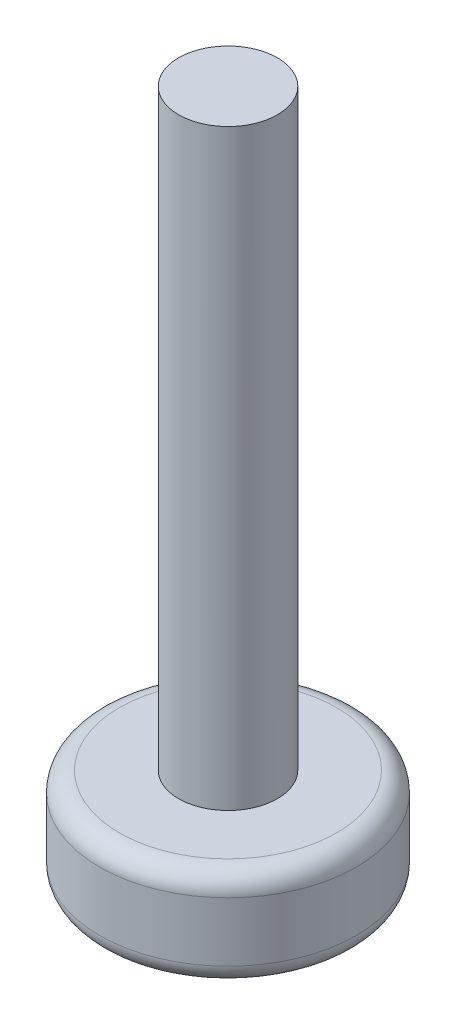
SolidWorks part; units mm, degrees
material "Nylon 101"
ref_plane "Front Plane" through (0, 0, 0) normal (0, 0, 1) x (1, 0, 0)
ref_plane "Top Plane" through (0, 0, 0) normal (0, 1, 0) x (1, 0, 0)
ref_plane "Right Plane" through (0, 0, 0) normal (1, 0, 0) x (0, 0, -1)
sketch "Sketch1" plane through (0, 0, 0) normal (0, 1, 0) x (1, 0, 0)
  circle A0 centre (0, 0) radius 2.5
  dimension "D1" = 5
extrude "Boss-Extrude1" add sketch "Sketch1" along normal blind 30
cosmetic thread "Cosmetic Thread1" parameters "D1"=30, "D2"=0.3
sketch "Sketch2" plane through (0, 0, 0) normal (0, 0, 1) x (1, 0, 0)
  line L0 (0, 0) -> (0, -5)
  line L1 (-5.5, 0) -> (0, 0)
  line L2 (-6.5, -1) -> (-6.5, -4)
  line L3 (-5.5, -5) -> (0, -5)
  arc A2 (-6.5, -4) -> (-5.5, -5) centre (-5.5, -4) ccw
  arc A3 (-5.5, 0) -> (-6.5, -1) centre (-5.5, -1) ccw
  point P9 (6.5, -5)
  point P12 (-6.5, -5)
  point P15 (-6.5, 0)
  dimension "D1" = 13
  dimension "D2" = 6.5
  dimension "D3" = 5
  dimension "D4" = 0
revolve "Revolve1" add sketch "Sketch2" angle 360 about L0
